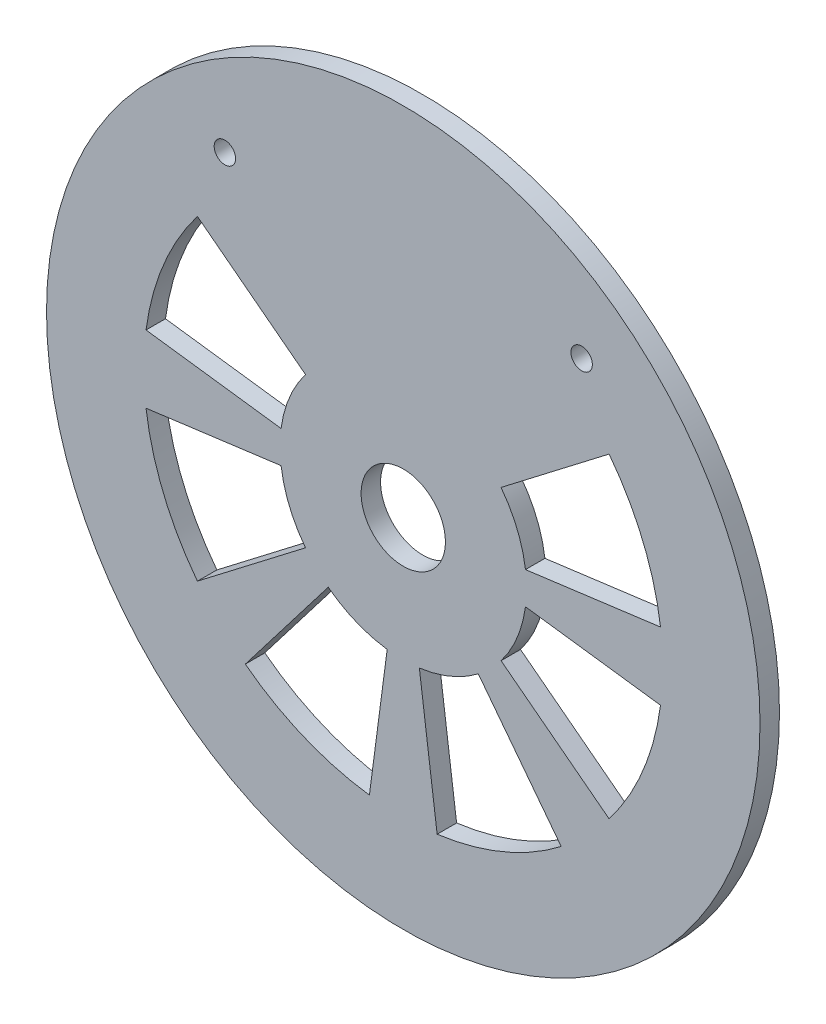
SolidWorks part; units mm, degrees
ref_plane "前视基准面" through (0, 0, 0) normal (0, 0, 1) x (1, 0, 0)
ref_plane "上视基准面" through (0, 0, 0) normal (0, 1, 0) x (1, 0, 0)
ref_plane "右视基准面" through (0, 0, 0) normal (1, 0, 0) x (0, 0, -1)
sketch "草图1" plane through (0, 0, 0) normal (0, 0, 1) x (1, 0, 0)
  circle A0 centre (0, 0) radius 55
  dimension "D1" = 110
extrude "凸台-拉伸1" add sketch "草图1" along normal blind 3
sketch "草图3" plane through (0, 0, 3) normal (0, 0, 1) x (1, 0, 0)
  line L0 (0, 68.3825) -> (0, -68.2401) construction
  line L1 (-60.1993, 35) -> (61.7648, 35) construction
  circle A2 centre (0, 0) radius 55 construction
  circle A3 centre (27.5, 35) radius 1.65
  circle A4 centre (-27.5, 35) radius 1.65
  dimension "D2" = 3.3
  dimension "D3" = 3.3
  dimension "D4" = 27.5
  dimension "D5" = 27.5
  dimension "D1" = 20
extrude "切除-拉伸1" cut sketch "草图3" against normal blind 3
sketch "草图4" plane through (0, 0, 3) normal (0, 0, 1) x (1, 0, 0)
  line L0 (0, 0) -> (39.6578, 5.221)
  line L1 (0, 0) -> (31.7341, 24.3505)
  line L2 (0, 0) -> (39.6578, -5.221)
  line L3 (0, 0) -> (31.7341, -24.3505)
  line L4 (0, 0) -> (24.3505, -31.7341)
  line L5 (0, 0) -> (5.221, -39.6578)
  line L6 (0, 0) -> (-5.221, -39.6578)
  line L7 (0, 0) -> (-24.3505, -31.7341)
  line L8 (0, 0) -> (-31.7341, -24.3505)
  line L9 (0, 0) -> (-39.6578, -5.221)
  line L10 (0, 0) -> (-39.6578, 5.221)
  line L11 (0, 0) -> (-31.7341, 24.3505)
  line L12 (0, 0) -> (-24.3505, 31.7341)
  line L13 (0, 0) -> (-5.221, 39.6578)
  line L14 (0, 0) -> (5.221, 39.6578)
  line L15 (0, 0) -> (24.3505, 31.7341)
  circle A0 centre (0, 0) radius 40
  circle A1 centre (0, 0) radius 55 construction
  circle A2 centre (0, 0) radius 19
  point P24 (0, 0)
  dimension "D1" = 15
  dimension "D2" = 38
  dimension "D3" = 30
  dimension "D4" = 7.5
  dimension "D5" = 8
extrude "切除-拉伸2" cut sketch "草图4" against normal blind 3 contours A2 L0 A0 L1 | A2 L11 A0 L10 | A2 L9 A0 L8 | A2 L7 A0 L6 | A2 L5 A0 L4 | A2 L3 A0 L2
sketch "草图5" plane through (0, 0, 3) normal (0, 0, 1) x (1, 0, 0)
  circle A0 centre (0, 0) radius 6.5
  dimension "D1" = 13
extrude "切除-拉伸3" cut sketch "草图5" against normal blind 3
